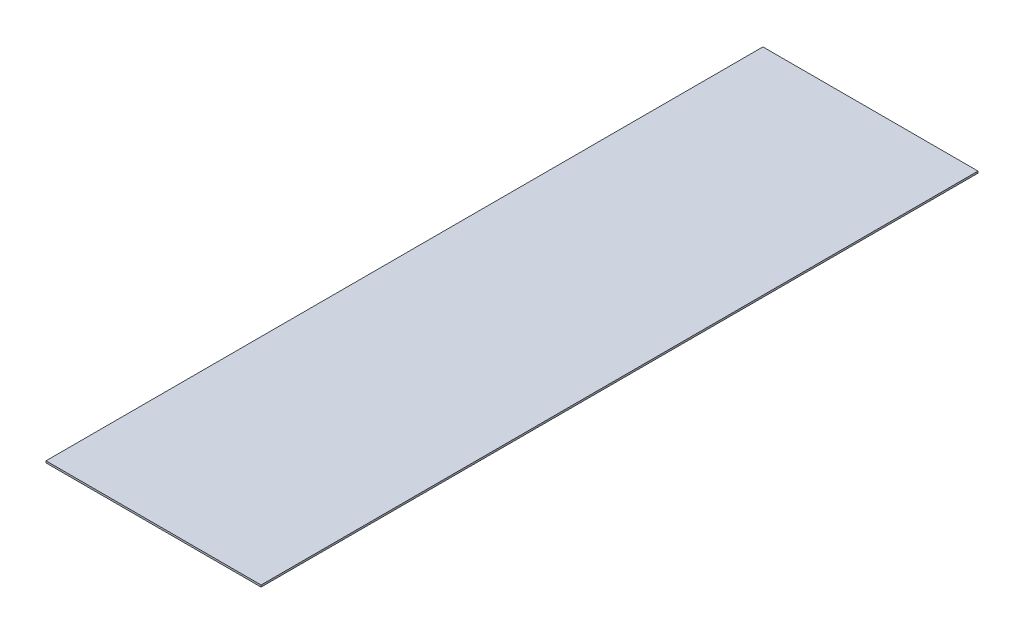
SolidWorks part; units mm, degrees
material "ASTM A36 Acero"
ref_plane "Alzado" through (0, 0, 0) normal (0, 0, 1) x (1, 0, 0)
ref_plane "Planta" through (0, 0, 0) normal (0, 1, 0) x (1, 0, 0)
ref_plane "Vista lateral" through (0, 0, 0) normal (1, 0, 0) x (0, 0, -1)
sketch "Croquis1" plane through (0, 0, 0) normal (0, 1, 0) x (1, 0, 0)
  line L1 (-457.2, -1524) -> (457.2, -1524)
  line L2 (-457.2, -1524) -> (-457.2, 1524)
  line L3 (-457.2, 1524) -> (457.2, 1524)
  line L4 (457.2, -1524) -> (457.2, 1524)
  line L5 (-457.2, -1524) -> (457.2, 1524) construction
  line L6 (-457.2, 1524) -> (457.2, -1524) construction
  point P0 (0, 0)
  dimension "D1" = 3048
  dimension "D2" = 914.4
extrude "Saliente-Extruir1" add sketch "Croquis1" along normal blind 7.9
